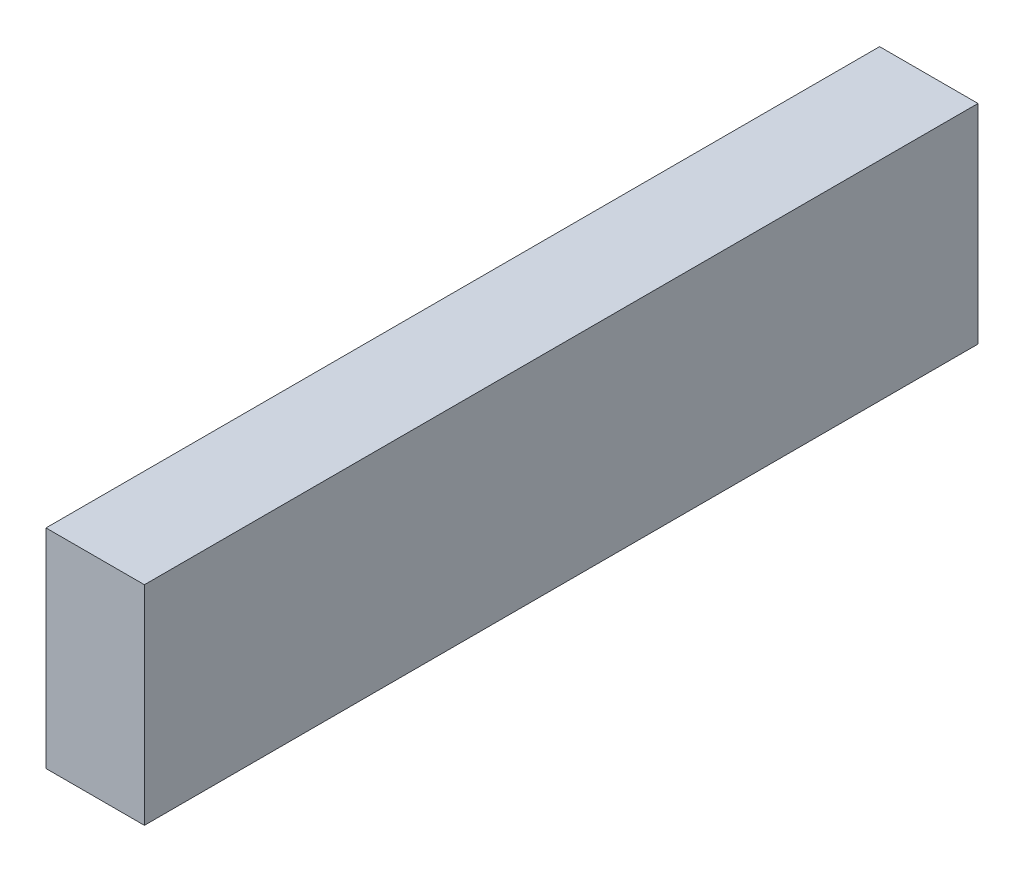
SolidWorks part; units mm, degrees
ref_plane "Front Plane" through (0, 0, 0) normal (0, 0, 1) x (1, 0, 0)
ref_plane "Top Plane" through (0, 0, 0) normal (0, 1, 0) x (1, 0, 0)
ref_plane "Right Plane" through (0, 0, 0) normal (1, 0, 0) x (0, 0, -1)
sketch "Sketch1" plane through (0, 0, 0) normal (0, 0, 1) x (1, 0, 0)
  line L1 (-8.9958, -19.05) -> (8.9958, -19.05)
  line L2 (-8.9958, -19.05) -> (-8.9958, 19.05)
  line L3 (-8.9958, 19.05) -> (8.9958, 19.05)
  line L4 (8.9958, -19.05) -> (8.9958, 19.05)
  line L5 (-8.9958, -19.05) -> (8.9958, 19.05) construction
  line L6 (-8.9958, 19.05) -> (8.9958, -19.05) construction
  point P0 (0, 0)
  dimension "D1" = 38.1
  dimension "D2" = 17.9917
extrude "Boss-Extrude1" add sketch "Sketch1" along normal mid plane 152.4
equation "\"D2@Sketch1\"=1.0625/1.5"
